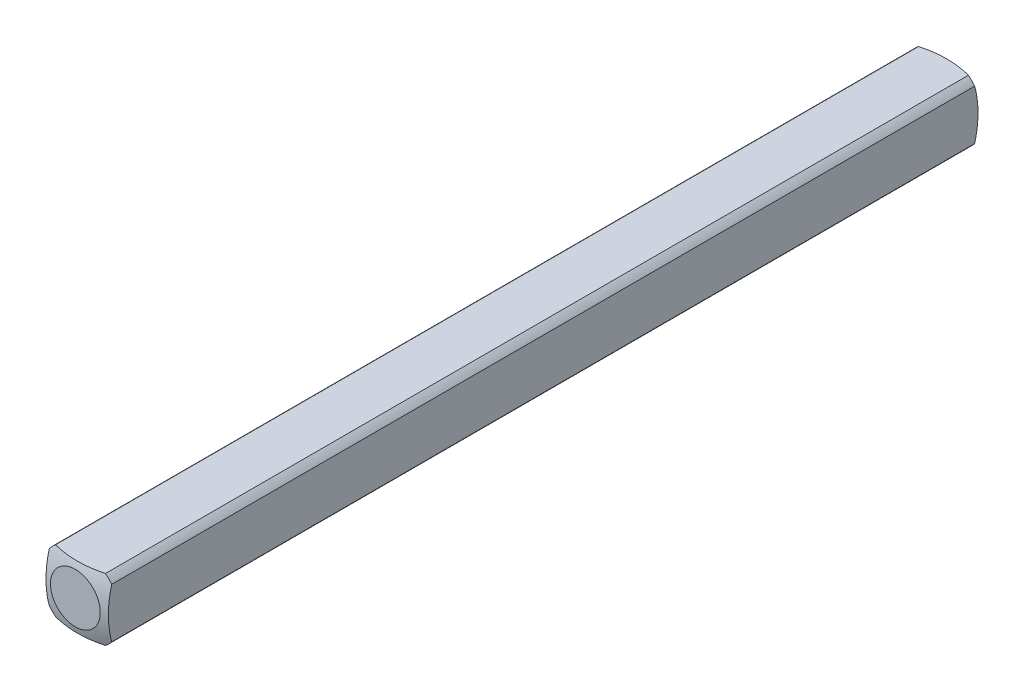
SolidWorks part; units mm, degrees
material "Custom Plastic"
ref_plane "Front Plane" through (0, 0, 0) normal (0, 0, 1) x (1, 0, 0)
ref_plane "Top Plane" through (0, 0, 0) normal (0, 1, 0) x (1, 0, 0)
ref_plane "Right Plane" through (0, 0, 0) normal (1, 0, 0) x (0, 0, -1)
sketch "Sketch1" plane through (0, 0, 0) normal (0, 0, 1) x (1, 0, 0)
  line L0 (-1.5875, -1.5875) -> (1.5875, 1.5875) construction
  line L1 (-1.5875, -1.5875) -> (1.5875, -1.5875)
  line L2 (-1.5875, -1.5875) -> (-1.5875, 1.5875)
  line L3 (-1.5875, 1.5875) -> (1.5875, 1.5875)
  line L4 (1.5875, -1.5875) -> (1.5875, 1.5875)
  dimension "D1" = 3.175
extrude "Boss-Extrude1" add sketch "Sketch1" along normal blind 22.225
sketch "Sketch2" plane through (0, 0, 0) normal (0, 0, -1) x (-1, 0, 0)
  circle A0 centre (0, 0) radius 2.032
  dimension "D1" = 4.064
extrude "Cut-Extrude1" cut sketch "Sketch2" against normal through all flip side to cut
ref_axis "Axis1" through (0, 0, 22.225) along (0, 0, -1)
sketch "Sketch3" plane through (0, 0, 0) normal (0, 1, 0) x (1, 0, 0)
  line L1 (-5.0537, -4.4027) -> (-5.0537, 5.7405)
  line L2 (-5.0537, 5.7405) -> (0, 5.7405)
  line L5 (0, -22.225) -> (0, 0) construction
  line L8 (0, 0.1609) -> (0, 5.7405)
  arc A0 (-5.0537, -4.4027) -> (0, 0.1609) centre (0, -4.9191) cw
  dimension "D1" = 5.08
revolve "Cut-Revolve1" cut sketch "Sketch3" angle 360 about axis through (0, 0, 22.225) along (0, 0, -1)
mirror "Mirror1" about plane through (0, 0, 22.225) normal (0, 0, -1) of bodies 103
